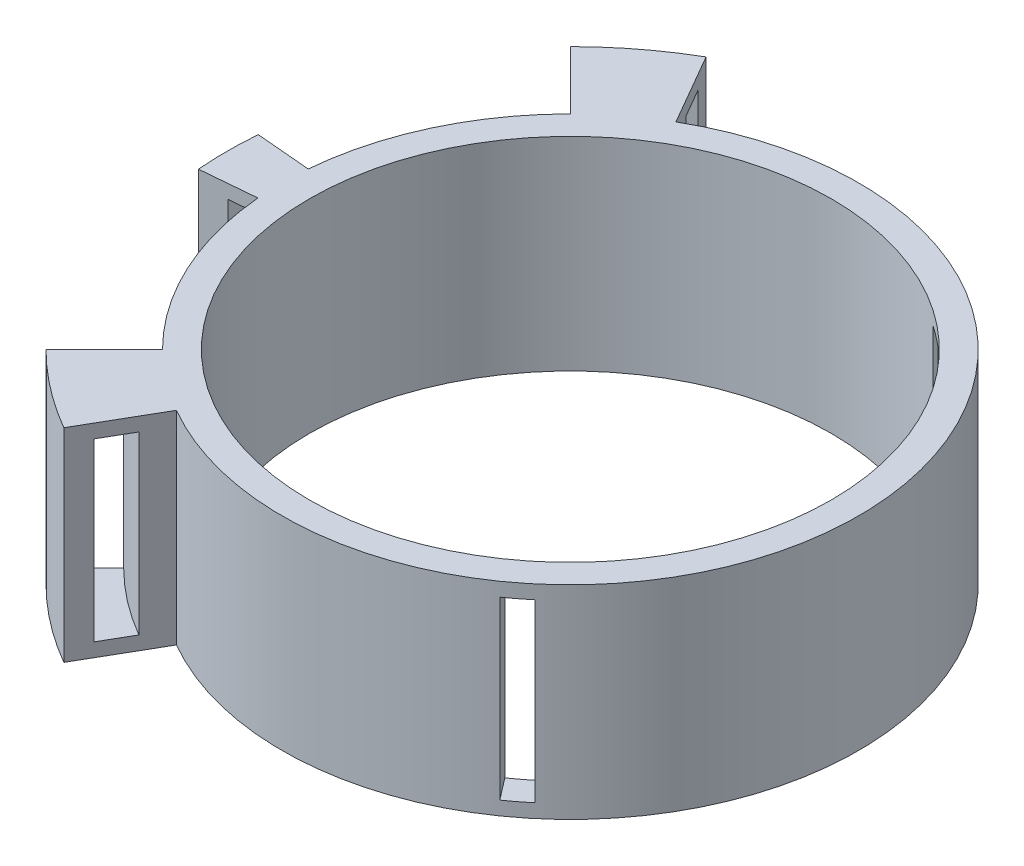
SolidWorks part; units mm, degrees
ref_plane "前视基准面" through (0, 0, 0) normal (0, 0, 1) x (1, 0, 0)
ref_plane "上视基准面" through (0, 0, 0) normal (0, 1, 0) x (1, 0, 0)
ref_plane "右视基准面" through (0, 0, 0) normal (1, 0, 0) x (0, 0, -1)
sketch "草图1" plane through (0, 0, 0) normal (0, 1, 0) x (1, 0, 0)
  line L0 (0, 0) -> (10.46, -0.9151) construction
  line L1 (0, 0) -> (10.46, 0.9151) construction
  line L2 (10.46, 0.9151) -> (9.4638, 0.828)
  line L3 (10.46, -0.9151) -> (9.4638, -0.828)
  line L5 (0, 0) -> (-4.75, -8.2272) construction
  line L6 (0, 0) -> (-6.7175, -6.7175) construction
  line L7 (0, 0) -> (-4.75, 8.2272) construction
  line L10 (0, 0) -> (-6.7175, 6.7175) construction
  line L11 (-7.4246, 7.4246) -> (-9.5459, 9.5459)
  line L12 (-5.25, 9.0933) -> (-6.75, 11.6913)
  line L13 (-7.4246, -7.4246) -> (-9.5459, -9.5459)
  line L14 (-5.25, -9.0933) -> (-6.75, -11.6913)
  line L15 (0, 0) -> (-14.5, 0) construction
  line L16 (0, 0) -> (-9.4638, 0.828) construction
  line L17 (0, 0) -> (-9.4638, -0.828) construction
  line L18 (-10.46, 0.9151) -> (-12.4524, 1.0894)
  line L19 (-10.46, -0.9151) -> (-12.4524, -1.0894)
  arc A0 (9.4638, 0.828) -> (9.4638, -0.828) centre (0, 0) ccw
  arc A1 (10.46, 0.9151) -> (-5.25, 9.0933) centre (0, 0) ccw
  arc A2 (-6.75, 11.6913) -> (-9.5459, 9.5459) centre (0, 0) ccw
  arc A3 (-9.5459, -9.5459) -> (-6.75, -11.6913) centre (0, 0) ccw
  arc A4 (-7.4246, 7.4246) -> (-10.46, 0.9151) centre (0, 0) ccw
  arc A5 (-5.25, -9.0933) -> (10.46, -0.9151) centre (0, 0) ccw
  arc A6 (-12.4524, 1.0894) -> (-12.4524, -1.0894) centre (0, 0) ccw
  arc A7 (-10.46, -0.9151) -> (-7.4246, -7.4246) centre (0, 0) ccw
extrude "凸台-拉伸1" add sketch "草图1" along normal blind 0.5
sketch "草图10" plane through (0, 0.5, 0) normal (0, 1, 0) x (1, 0, 0)
  line L0 (0, 0) -> (9.4638, -0.828) construction
  line L1 (9.4638, -0.828) -> (10.46, -0.9151)
  line L2 (9.4638, 0.828) -> (10.46, 0.9151)
  line L3 (0, 0) -> (6.7493, -8.0435) construction
  line L4 (6.7493, -8.0435) -> (6.0275, -8.5977) construction
  line L5 (6.0275, -8.5977) -> (5.4178, -7.8037) construction
  line L6 (6.7493, -8.0435) -> (6.1065, -7.2774)
  line L7 (6.0275, -8.5977) -> (5.4178, -7.8037)
  line L8 (0, 0) -> (6.7092, 8.0769) construction
  line L9 (6.7092, 8.0769) -> (5.9838, 8.6281) construction
  line L10 (5.9838, 8.6281) -> (5.3782, 7.831) construction
  line L11 (5.3782, 7.831) -> (5.9838, 8.6281)
  line L12 (6.7092, 8.0769) -> (6.0702, 7.3077)
  arc A0 (9.4638, 0.828) -> (6.0702, 7.3077) centre (0, 0) ccw
  arc A1 (10.46, 0.9151) -> (6.7092, 8.0769) centre (0, 0) ccw
  arc A2 (10.46, 0.9151) -> (-5.25, 9.0933) centre (0, 0) ccw construction
  arc A3 (6.1065, -7.2774) -> (9.4638, -0.828) centre (0, 0) ccw
  arc A4 (6.7493, -8.0435) -> (10.46, -0.9151) centre (0, 0) ccw
  arc A5 (5.3782, 7.831) -> (5.4178, -7.8037) centre (0, 0) ccw
  arc A6 (5.9838, 8.6281) -> (6.0275, -8.5977) centre (0, 0) ccw
  arc M10 (10.46, 0.9151) -> (-5.25, 9.0933) centre (0, 0) ccw
  line M11 (10.46, -0.9151) -> (9.4638, -0.828)
  arc M12 (9.4638, -0.828) -> (9.4638, 0.828) centre (0, 0) cw
  line M13 (9.4638, 0.828) -> (10.46, 0.9151)
extrude "凸台-拉伸2" add sketch "草图10" along normal blind 6.4 contours L6 M10 M11 M12 | L11 L7 M12 M10 | L12 M10 M12 M13
sketch "草图11" plane through (0, 6.9, 0) normal (0, 1, 0) x (1, 0, 0)
  line L0 (10.46, -0.9151) -> (9.4638, -0.828) construction
  line L1 (9.4638, 0.828) -> (10.46, 0.9151)
  line L2 (9.4638, -0.828) -> (10.46, -0.9151)
  arc A0 (9.4638, 0.828) -> (9.4638, -0.828) centre (0, 0) ccw
  arc A1 (10.46, 0.9151) -> (10.46, -0.9151) centre (0, 0) ccw
  arc A2 (6.7493, -8.0435) -> (10.46, -0.9151) centre (0, 0) ccw construction
extrude "凸台-拉伸3" add sketch "草图11" along normal blind 0.5
sketch "草图12" plane through (0, 0.5, 0) normal (0, 1, 0) x (1, 0, 0)
  line L2 (0.3536, 0.3536) -> (-5.1431, 0.3536) construction
  line L14 (-12.4524, 1.0894) -> (-11.4562, 1.0023)
  line L18 (-10.46, 0.9151) -> (-12.4524, 1.0894) construction
  line L21 (-12.4524, -1.0894) -> (-11.4562, -1.0023)
  line L22 (-12.4524, -1.0894) -> (-10.46, -0.9151) construction
  line L23 (-9.5459, -9.5459) -> (-8.9803, -8.9803)
  line L24 (-7.4246, -7.4246) -> (-9.5459, -9.5459) construction
  line L25 (-6.75, -11.6913) -> (-6.35, -10.9985)
  line L26 (-6.75, -11.6913) -> (-5.25, -9.0933) construction
  line L27 (-7.4246, -7.4246) -> (-8.1317, -8.1317)
  line L28 (-5.25, -9.0933) -> (-5.75, -9.9593)
  line L29 (-9.5459, 9.5459) -> (-8.9803, 8.9803)
  line L30 (-9.5459, 9.5459) -> (-7.4246, 7.4246) construction
  line L31 (-6.75, 11.6913) -> (-6.35, 10.9985)
  line L32 (-5.25, 9.0933) -> (-6.75, 11.6913) construction
  line L33 (-7.4246, 7.4246) -> (-8.1317, 8.1317)
  line L34 (-5.25, 9.0933) -> (-5.75, 9.9593)
  arc A11 (-12.4524, 1.0894) -> (-12.4524, -1.0894) centre (0, 0) ccw
  arc A13 (-11.4562, 1.0023) -> (-11.4562, -1.0023) centre (0, 0) ccw
  arc A14 (-9.5459, -9.5459) -> (-6.75, -11.6913) centre (0, 0) ccw
  arc A15 (-8.9803, -8.9803) -> (-6.35, -10.9985) centre (0, 0) ccw
  arc A16 (-7.4246, -7.4246) -> (-5.25, -9.0933) centre (0, 0) ccw
  arc A17 (-8.1317, -8.1317) -> (-5.75, -9.9593) centre (0, 0) ccw
  arc A18 (-9.5459, 9.5459) -> (-6.75, 11.6913) centre (0, 0) cw
  arc A19 (-8.9803, 8.9803) -> (-6.35, 10.9985) centre (0, 0) cw
  arc A20 (-8.1317, 8.1317) -> (-5.75, 9.9593) centre (0, 0) cw
  arc A21 (-7.4246, 7.4246) -> (-5.25, 9.0933) centre (0, 0) cw
sketch "草图14" plane through (0, 7.4, 0) normal (0, 1, 0) x (1, 0, 0)
  line L0 (9.4638, 0.828) -> (10.46, 0.9151) construction
  line L1 (9.4638, 0.828) -> (10.46, 0.9151)
  line L2 (9.4638, -0.828) -> (10.46, -0.9151)
  arc A0 (9.4638, -0.828) -> (9.4638, 0.828) centre (0, 0) ccw
  arc A1 (10.46, -0.9151) -> (10.46, 0.9151) centre (0, 0) ccw
extrude "凸台-拉伸6" add sketch "草图14" against normal blind 7.4
extrude "凸台-拉伸7" add sketch "草图12" along normal blind 6.4
sketch "草图15" plane through (0, 6.9, 0) normal (0, 1, 0) x (1, 0, 0)
  line L2 (-12.4524, 1.0894) -> (-10.46, 0.9151)
  line L3 (-11.4562, 1.0023) -> (-12.4524, 1.0894) construction
  line L4 (-12.4524, -1.0894) -> (-10.46, -0.9151)
  line L5 (-12.4524, -1.0894) -> (-11.4562, -1.0023) construction
  line L6 (-9.5459, -9.5459) -> (-7.4246, -7.4246)
  line L7 (-6.75, -11.6913) -> (-5.25, -9.0933)
  line L8 (-9.5459, 9.5459) -> (-7.4246, 7.4246)
  line L9 (-6.75, 11.6913) -> (-5.25, 9.0933)
  arc A1 (-12.4524, -1.0894) -> (-12.4524, 1.0894) centre (0.5018, 0) cw
  arc A2 (-10.46, 0.9151) -> (-10.46, -0.9151) centre (0, 0) ccw
  arc A3 (-7.4246, -7.4246) -> (-5.25, -9.0933) centre (0, 0) ccw
  arc A4 (-9.5459, -9.5459) -> (-6.75, -11.6913) centre (0, 0) ccw
  arc A5 (-6.75, 11.6913) -> (-9.5459, 9.5459) centre (0, 0) ccw
  arc A6 (-5.25, 9.0933) -> (-7.4246, 7.4246) centre (0, 0) ccw
extrude "凸台-拉伸8" add sketch "草图15" along normal blind 0.5
